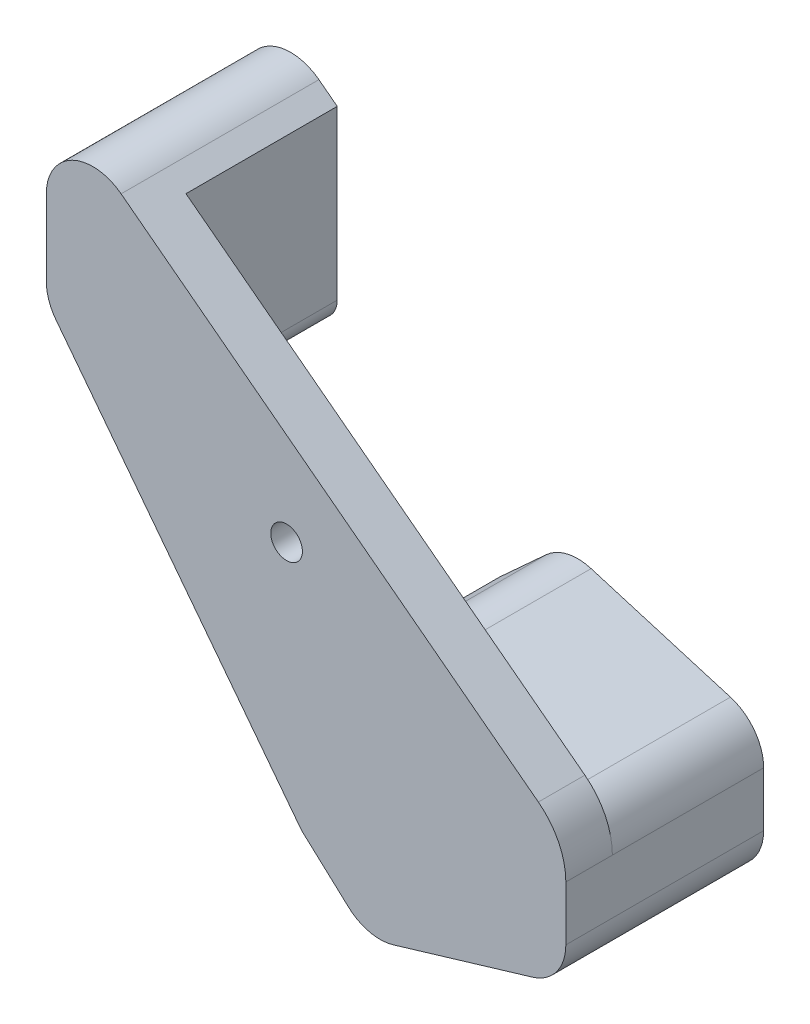
SolidWorks part; units mm, degrees
ref_plane "Front Plane" through (0, 0, 0) normal (0, 0, 1) x (1, 0, 0)
ref_plane "Top Plane" through (0, 0, 0) normal (0, 1, 0) x (1, 0, 0)
ref_plane "Right Plane" through (0, 0, 0) normal (1, 0, 0) x (0, 0, -1)
sketch "Sketch1" plane through (0, 0, 0) normal (0, 0, 1) x (1, 0, 0)
  line L0 (0, 0) -> (0, 12.7)
  line L1 (0, 12.7) -> (11.1125, 22.86)
  line L3 (11.1125, 22.86) -> (38.1, 14.7942)
  line L4 (38.1, 14.7942) -> (38.1, -19.05)
  line L5 (11.1125, 12.7) -> (11.1125, 0) construction
  line L6 (11.1125, 6.35) -> (30.1625, 6.35) construction
  line L7 (11.1125, -10.16) -> (38.1, -2.0942)
  line L8 (0, 0) -> (11.1125, -10.16)
  circle A0 centre (11.1125, 12.7) radius 2.032
  circle A1 centre (11.1125, 0) radius 2.032
  circle A2 centre (30.1625, 6.35) radius 2.032
  dimension "D3" = 4.064
  dimension "D1" = 73.36
  dimension "D2" = 38.1
  dimension "D4" = 11.1125
  dimension "D5" = 12.7
  dimension "D6" = 10.16
  dimension "D7" = 19.05
  dimension "D8" = 19.05
extrude "Boss-Extrude1" add sketch "Sketch1" along normal blind 20.6375 contours L0 L8 L7 L4 L3 L1 A2 A1 A0
fillet "Fillet1" radius 6.35 6 edges at (38.1, 14.7942, 10.3187) (11.1125, 22.86, 10.3187) (0, 12.7, 10.3187) (38.1, -2.0942, 10.3187) (11.1125, -10.16, 10.3187) (0, 0, 10.3187)
sketch "Sketch3" plane through (0, 0, 20.6375) normal (0, 0, 1) x (1, 0, 0)
  line L0 (2.0652, -1.8882) -> (-32.7759, 43.4132)
  line L1 (-32.7759, 43.4132) -> (-32.7759, 68.8132)
  line L2 (-32.7759, 68.8132) -> (34.3497, 17.6393)
  line L6 (14.5601, -9.1296) -> (33.5684, -3.4485)
  line L7 (38.1, 2.6355) -> (38.1, 10.0645)
  line L8 (33.5684, 16.1485) -> (14.5601, 21.8296)
  line L9 (8.4569, 20.432) -> (2.0652, 14.5882)
  line L10 (0, 9.9017) -> (0, 2.7983)
  line L11 (2.0652, -1.8882) -> (8.4569, -7.732)
  line L12 (14.5601, -9.1296) -> (33.5684, -3.4485)
  line L13 (38.1, 2.6355) -> (38.1, 10.0645)
  line L17 (2.0652, -1.8882) -> (8.4569, -7.732)
  arc A0 (38.1, 10.0645) -> (34.3497, 17.6393) centre (28.575, 10.0645) ccw
  circle A1 centre (0, 31.1519) radius 2.159 construction
  circle A2 centre (0, 31.1519) radius 2.159
  arc A6 (33.5684, -3.4485) -> (38.1, 2.6355) centre (31.75, 2.6355) ccw
  arc A7 (38.1, 10.0645) -> (33.5684, 16.1485) centre (31.75, 10.0645) ccw
  arc A8 (14.5601, 21.8296) -> (8.4569, 20.432) centre (12.7417, 15.7455) ccw
  arc A9 (2.0652, 14.5882) -> (0, 9.9017) centre (6.35, 9.9017) ccw
  arc A10 (0, 2.7983) -> (2.0652, -1.8882) centre (6.35, 2.7983) ccw
  arc A11 (8.4569, -7.732) -> (14.5601, -9.1296) centre (12.7417, -3.0455) ccw
  arc A12 (33.5684, -3.4485) -> (38.1, 2.6355) centre (31.75, 2.6355) ccw
  arc A17 (8.4569, -7.732) -> (14.5601, -9.1296) centre (12.7417, -3.0455) ccw
  dimension "D2" = 57.15
  dimension "D3" = 9.525
  dimension "D4" = 170
  dimension "D5" = 25.4
  dimension "D1" = 0
extrude "Boss-Extrude2" add sketch "Sketch3" along normal blind 6.35
fillet "Fillet2" radius 6.35 2 edges at (-32.7759, 43.4132, 23.8125) (-32.7759, 68.8132, 23.8125)
sketch "Sketch4" plane through (0, 0, 20.6375) normal (0, 0, -1) x (-1, 0, 0)
  line L0 (32.7759, 55.9874) -> (32.7759, 45.5727) construction
  line L1 (32.7759, 55.9874) -> (32.7759, 45.5727)
  line L2 (22.5761, 61.0373) -> (20.0759, 59.1312)
  line L3 (-34.3497, 17.6393) -> (22.5761, 61.0373) construction
  line L4 (31.4594, 41.7014) -> (20.0759, 26.9003)
  line L5 (20.0759, 59.1312) -> (20.0759, 26.9003)
  arc A0 (31.4594, 41.7014) -> (32.7759, 45.5727) centre (26.4259, 45.5727) ccw construction
  arc A1 (32.7759, 55.9874) -> (22.5761, 61.0373) centre (26.4259, 55.9874) ccw construction
  arc A2 (31.4594, 41.7014) -> (32.7759, 45.5727) centre (26.4259, 45.5727) ccw
  arc A3 (32.7759, 55.9874) -> (22.5761, 61.0373) centre (26.4259, 55.9874) ccw
  circle A4 centre (26.4259, 55.9874) radius 2.032
  circle A5 centre (26.4259, 45.5727) radius 2.032
  dimension "D2" = 4.064
  dimension "D1" = 12.7
extrude "Boss-Extrude3" add sketch "Sketch4" along normal up to surface (20.6375 mm away)
ref_plane "Plane1" through (0, 0, -2.54) normal (0, 0, -1) x (-1, 0, 0)
fillet "Fillet3" radius 3.175 1 edges at (-20.0759, 26.9003, 10.3187)
mirror "Mirror2" [suppressed] about plane through (0, 0, -2.54) normal (0, 0, -1)
delete or keep bodies "Body-Delete/Keep 1" [suppressed] type delete bodies bodies 103
